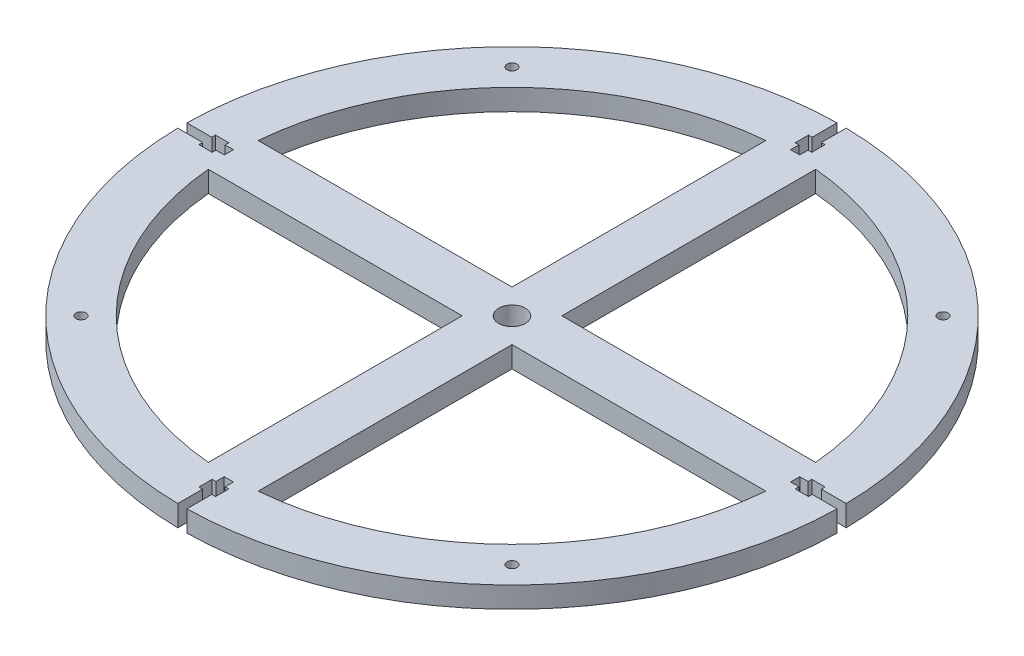
SolidWorks part; units mm, degrees
material "6061 Alloy"
ref_plane "Front Plane" through (0, 0, 0) normal (0, 0, 1) x (1, 0, 0)
ref_plane "Top Plane" through (0, 0, 0) normal (0, 1, 0) x (1, 0, 0)
ref_plane "Right Plane" through (0, 0, 0) normal (1, 0, 0) x (0, 0, -1)
sketch "Sketch1" plane through (0, 0, 0) normal (0, 1, 0) x (1, 0, 0)
  line L0 (0, -99.238) -> (0, 99.238) construction
  line L1 (-99.238, 0) -> (99.238, 0) construction
  line L2 (-98.9542, -7.5) -> (98.9542, -7.5)
  line L3 (7.5, -98.9542) -> (7.5, 98.9542)
  line L4 (-98.9542, 7.5) -> (98.9542, 7.5)
  line L5 (-7.5, -98.9542) -> (-7.5, 98.9542)
  line L6 (-7.5, -99.238) -> (-7.5, 99.238) construction
  line L7 (7.5, -99.238) -> (7.5, 99.238) construction
  line L8 (-99.238, -7.5) -> (99.238, -7.5) construction
  line L9 (-99.238, 7.5) -> (99.238, 7.5) construction
  circle A0 centre (0, 0) radius 100 construction
  circle A1 centre (0, 0) radius 99.238
  circle A2 centre (0, 0) radius 84.238
  point P7 (0, 0)
  point P11 (0, 0)
  dimension "D1" = 200
  dimension "D2" = 0.762
  dimension "D3" = 15
  dimension "D4" = 7.5
  dimension "D5" = 7.5
extrude "Boss-Extrude1" add sketch "Sketch1" along normal mid plane 6.35 contours A2 L2 A1 L5 | A2 L4 A1 L2 | A2 L5 A1 L4 | A2 L3 A1 L5 | A2 L4 A1 L3 | A2 L2 A1 L4 | A2 L3 A1 L2 | A2 L5 A1 L3 | L5 A2 L3 L2 | L4 A2 L2 L5 | L3 A2 L5 L4 | L2 A2 L4 L3 | L5 L2 L3 L4
sketch "Sketch2" plane through (0, 0, 0) normal (0, 1, 0) x (1, 0, 0)
  line L0 (-1.375, 85.238) -> (-1.375, 99.238)
  line L1 (-1.375, 85.238) -> (1.375, 85.238)
  line L2 (-1.375, 99.238) -> (1.375, 99.238)
  line L3 (1.375, 85.238) -> (1.375, 99.238)
  line L4 (-1.375, 85.238) -> (1.375, 99.238) construction
  line L5 (-1.375, 99.238) -> (1.375, 85.238) construction
  line L6 (-2.5, 87.738) -> (-2.5, 91.738)
  line L7 (-2.5, 87.738) -> (2.5, 87.738)
  line L8 (-2.5, 91.738) -> (2.5, 91.738)
  line L9 (2.5, 87.738) -> (2.5, 91.738)
  line L10 (-2.5, 87.738) -> (2.5, 91.738) construction
  line L11 (-2.5, 91.738) -> (2.5, 87.738) construction
  line L12 (0, -1000) -> (0, 49000) construction
  line L13 (-1000, 0) -> (49000, 0) construction
  circle A0 centre (0, 0) radius 99.238 construction
  point P1 (0, 92.238)
  point P2 (0, 89.738)
  dimension "D1" = 2.75
  dimension "D2" = 14
  dimension "D3" = 4
  dimension "D4" = 5
  dimension "D5" = 2.5
extrude "Cut-Extrude1" cut sketch "Sketch2" against normal through all both and the other way through all contours L7 L0 L1 L3 | L8 L0 L7 L3 | L7 L9 L8 L3 | L0 L8 L3 L2 | L8 L6 L7 L0
pattern_circular "CirPattern1" count 4 over 360 about axis through (0, 0, 0) along (0, 1, 0) of "Cut-Extrude1"
hole_wizard "Ø3.0 (3) Diameter Hole1" positions "Sketch3" profile "Sketch4" hole size "Ø3.0" standard "ANSI Metric" end condition up to next
sketch "Sketch3" plane through (0, 3.175, 0) normal (0, 1, 0) x (1, 0, 0)
  line L0 (-70.1719, -70.1719) -> (70.1719, 70.1719) construction
  line L2 (-70.1719, 70.1719) -> (70.1719, -70.1719) construction
  line L4 (70.1719, 70.1719) -> (59.5653, 59.5653)
  line L6 (70.1719, -70.1719) -> (59.5653, -59.5653)
  line L8 (-70.1719, -70.1719) -> (-59.5653, -59.5653)
  line L10 (-70.1719, 70.1719) -> (-59.5653, 59.5653)
  arc A0 (99.2285, 1.375) -> (1.375, 99.2285) centre (0, 0) ccw construction
  arc A1 (1.375, -99.2285) -> (99.2285, -1.375) centre (0, 0) ccw construction
  arc A2 (83.9035, 7.5) -> (7.5, 83.9035) centre (0, 0) ccw construction
  arc A3 (7.5, -83.9035) -> (83.9035, -7.5) centre (0, 0) ccw construction
  arc A4 (-83.9035, -7.5) -> (-7.5, -83.9035) centre (0, 0) ccw construction
  arc A5 (-7.5, 83.9035) -> (-83.9035, 7.5) centre (0, 0) ccw construction
  point P107 (0, 0)
  point P324 (0, 0)
  point P360 (-64.8686, 64.8686)
  point P362 (64.8686, 64.8686)
  point P364 (64.8686, -64.8686)
  point P366 (-64.8686, -64.8686)
sketch "Sketch4" plane through (-64.8686, 3.175, 64.8686) normal (1, 0, 0) x (0, 0, 1)
  line L0 (0, 0) -> (0, 6.35)
  line L1 (0, 6.35) -> (1.5, 6.35)
  line L2 (1.5, 6.35) -> (1.5, 0)
  line L5 (1.5, 0) -> (0, 0)
  line L11 (0, -6.35) -> (0, 107.95) construction
  dimension "Thru Hole Dia." = 3
  dimension "Thru Hole Depth" = 6.35
hole_wizard "Ø8.0 (8) Diameter Hole1" positions "Sketch5" profile "Sketch6" hole size "Ø8.0" standard "ANSI Metric" end condition up to next
sketch "Sketch5" plane through (0, 3.175, 0) normal (0, 1, 0) x (1, 0, 0)
  point P0 (0, 0)
sketch "Sketch6" plane through (0, 3.175, 0) normal (1, 0, 0) x (0, 0, 1)
  line L0 (0, 0) -> (0, 6.35)
  line L1 (0, 6.35) -> (4, 6.35)
  line L2 (4, 6.35) -> (4, 0)
  line L5 (4, 0) -> (0, 0)
  line L11 (0, -6.35) -> (0, 107.95) construction
  dimension "Thru Hole Dia." = 8
  dimension "Thru Hole Depth" = 6.35
